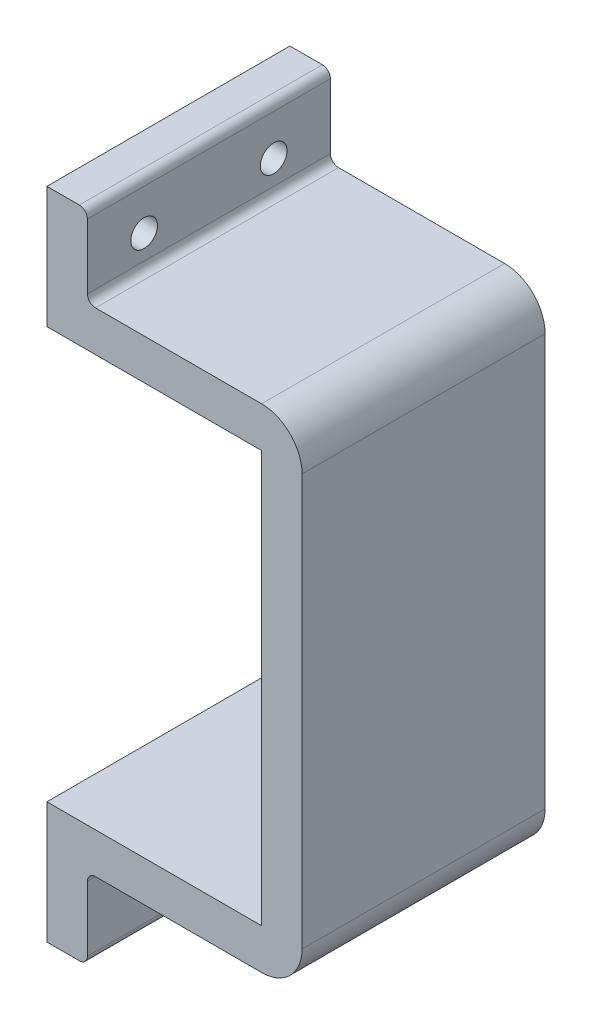
SolidWorks part; units mm, degrees
ref_plane "Front Plane" through (0, 0, 0) normal (0, 0, 1) x (1, 0, 0)
ref_plane "Top Plane" through (0, 0, 0) normal (0, 1, 0) x (1, 0, 0)
ref_plane "Right Plane" through (0, 0, 0) normal (1, 0, 0) x (0, 0, -1)
sketch "Sketch1" plane through (0, 0, 0) normal (0, 0, 1) x (1, 0, 0)
  line L0 (-13.25, 25.4) -> (-13.25, 40.4)
  line L1 (-13.25, 25.4) -> (13.25, 25.4)
  line L2 (-13.25, 25.4) -> (-13.25, -25.4)
  line L3 (-13.25, -25.4) -> (13.25, -25.4)
  line L4 (13.25, 25.4) -> (13.25, -25.4)
  line L5 (-13.25, 25.4) -> (13.25, -25.4) construction
  line L6 (-13.25, -25.4) -> (13.25, 25.4) construction
  line L7 (-13.25, 40.4) -> (-8.25, 40.4)
  line L8 (-8.25, 40.4) -> (-8.25, 30.4)
  line L9 (-8.25, 30.4) -> (18.25, 30.4)
  line L10 (18.25, 30.4) -> (18.25, -30.4)
  line L11 (18.25, -30.4) -> (-8.25, -30.4)
  line L12 (-8.25, -30.4) -> (-8.25, -40.4)
  line L13 (-8.25, -40.4) -> (-13.25, -40.4)
  line L14 (-13.25, -40.4) -> (-13.25, -25.4)
  line L15 (-13.25, -25.4) -> (13.25, -25.4)
  point P0 (0, 0)
  dimension "D1" = 26.5
  dimension "D2" = 50.8
  dimension "D3" = 15
  dimension "D4" = 5
  dimension "D5" = 15
  dimension "D6" = 5
  dimension "D7" = 5
  dimension "D8" = 5
  dimension "D9" = 5
extrude "Boss-Extrude1" add sketch "Sketch1" along normal blind 30 contours L14 L13 L12 L11 L10 L9 L8 L7 L0 L1 L4 L3
sketch "Sketch2" plane through (-13.25, 0, 0) normal (-1, 0, 0) x (0, 0, 1)
  line L0 (0, 25.4) -> (0, 40.4) construction
  line L1 (0, 25.4) -> (30, 25.4)
  line L2 (0, 25.4) -> (0, -25.4)
  line L3 (0, -25.4) -> (30, -25.4)
  line L4 (30, 25.4) -> (30, -25.4)
  line L5 (30, 25.4) -> (30, 40.4) construction
  line L7 (0, -40.4) -> (0, -25.4) construction
  line L8 (30, -40.4) -> (30, -25.4) construction
  circle A0 centre (7, 34.4) radius 1.65
  circle A1 centre (23, 34.4) radius 1.65
  circle A2 centre (7, -34.4) radius 1.65
  circle A3 centre (23, -34.4) radius 1.65
  dimension "D1" = 9
  dimension "D2" = 7
  dimension "D3" = 7
  dimension "D4" = 9
  dimension "D5" = 3.3
  dimension "D6" = 3.3
  dimension "D7" = 9
  dimension "D8" = 7
  dimension "D9" = 9
  dimension "D10" = 7
  dimension "D11" = 3.3
  dimension "D12" = 3.3
extrude "Cut-Extrude2" cut sketch "Sketch2" against normal blind 30 contours A0 | A1 | A2 | A3
fillet "Fillet1" radius 5 2 edges at (18.25, -30.4, 15) (18.25, 30.4, 15)
fillet "Fillet2" radius 1 4 edges at (-8.25, -30.4, 15) (-8.25, -40.4, 15) (-8.25, 30.4, 15) (-8.25, 40.4, 15)
